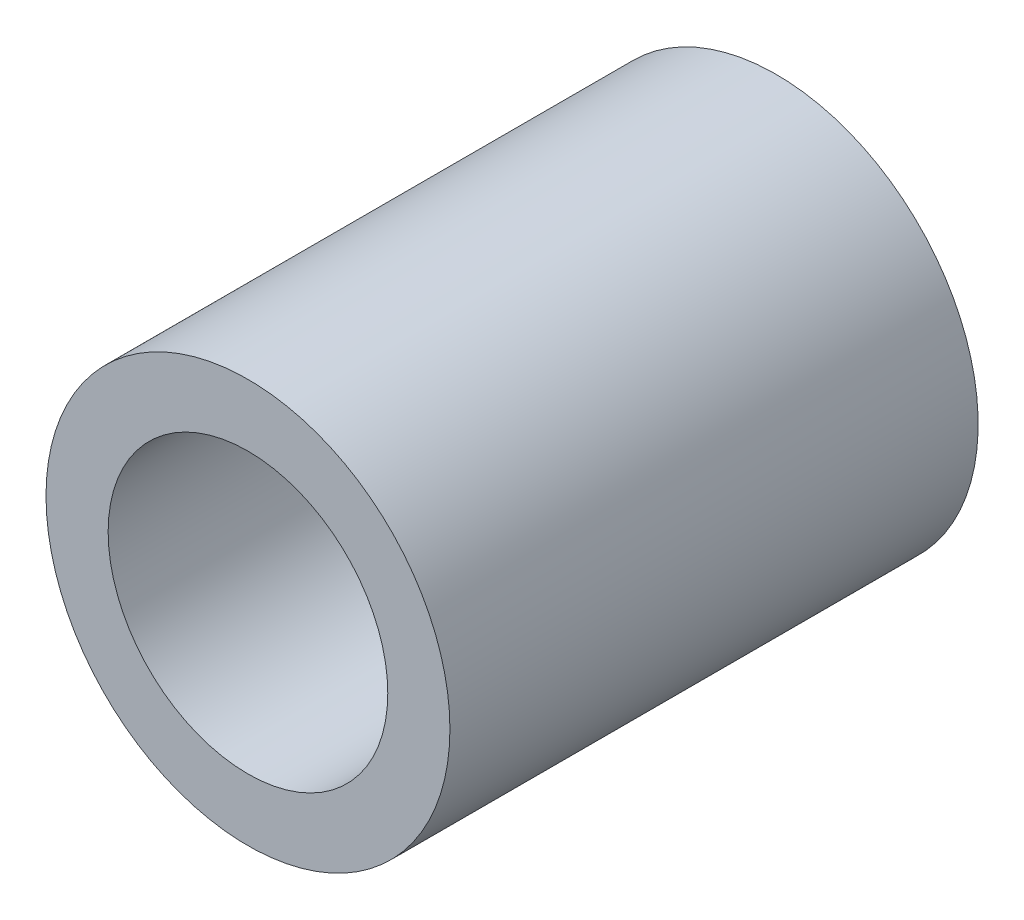
SolidWorks part; units mm, degrees
ref_plane "Ön Düzlem" through (0, 0, 0) normal (0, 0, 1) x (1, 0, 0)
ref_plane "Üst Düzlem" through (0, 0, 0) normal (0, 1, 0) x (1, 0, 0)
ref_plane "Sağ Düzlem" through (0, 0, 0) normal (1, 0, 0) x (0, 0, -1)
sketch "Sketch1" plane through (0, 0, 0) normal (0, 0, 1) x (1, 0, 0)
  circle A0 centre (0, 0) radius 4.5
  circle A1 centre (0, 0) radius 6.5
  dimension "D1" = 9
  dimension "D2" = 13
extrude "Boss-Extrude1" add sketch "Sketch1" along normal blind 15
sketch "Sketch2" plane through (0, 0, 0) normal (0, 0, -1) x (-1, 0, 0)
  circle A0 centre (0, 0) radius 6.5
  circle A1 centre (0, 0) radius 3.2232
extrude "Boss-Extrude2" add sketch "Sketch2" along normal blind 2 and the other way blind 3
